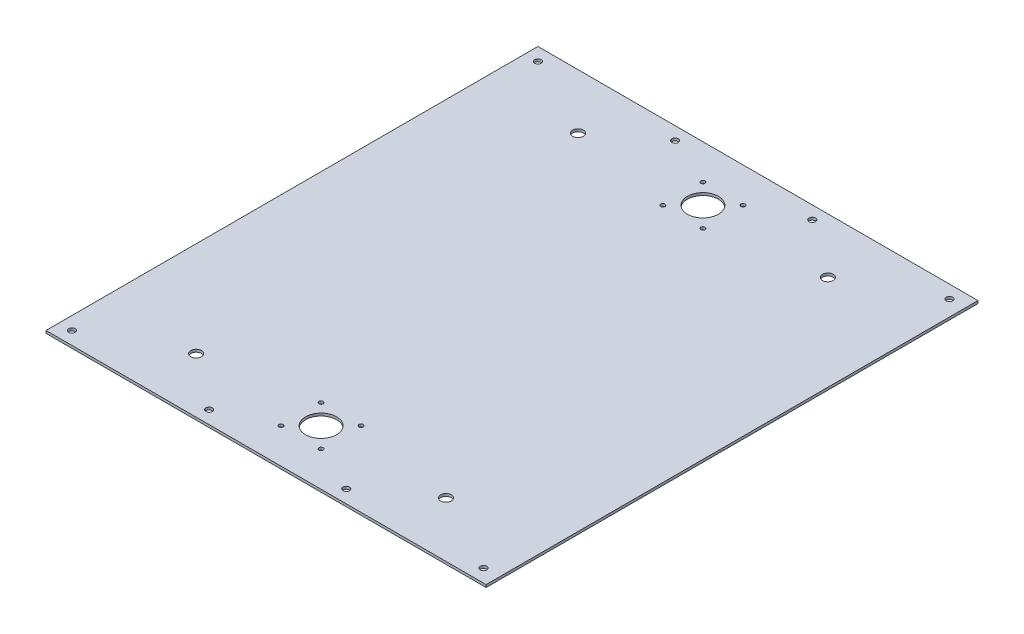
SolidWorks part; units mm, degrees
material "3.0526 (EN-AW 3004)"
ref_plane "Přední rovina" through (0, 0, 0) normal (0, 0, 1) x (1, 0, 0)
ref_plane "Horní rovina" through (0, 0, 0) normal (0, 1, 0) x (1, 0, 0)
ref_plane "Pravá rovina" through (0, 0, 0) normal (1, 0, 0) x (0, 0, -1)
sketch "Skica1" plane through (0, 0, 0) normal (0, 1, 0) x (1, 0, 0)
  line L1 (170, -190) -> (-170, -190)
  line L2 (170, -190) -> (170, 190)
  line L3 (170, 190) -> (-170, 190)
  line L4 (-170, -190) -> (-170, 190)
  line L5 (170, -190) -> (-170, 190) construction
  line L6 (170, 190) -> (-170, -190) construction
  circle A0 centre (-160, 180) radius 2.5
  circle A1 centre (-54, 180) radius 2.5
  circle A2 centre (52, 180) radius 2.5
  circle A3 centre (158, 180) radius 2.5
  circle A4 centre (-54, -180) radius 2.5
  circle A5 centre (52, -180) radius 2.5
  circle A6 centre (158, -180) radius 2.5
  circle A7 centre (-160, -180) radius 2.5
  point P0 (0, 0)
  dimension "D5" = 5
  dimension "D1" = 340
  dimension "D2" = 380
  dimension "D3" = 10
  dimension "D4" = 10
  dimension "D6" = 4
  dimension "D7" = 2
extrude "Přidat vysunutím1" add sketch "Skica1" along normal blind 2
sketch "Skica2" plane through (0, 0, 0) normal (0, -1, 0) x (1, 0, 0)
  circle A0 centre (15.5, 163) radius 1.65
  circle A1 centre (-15.5, 163) radius 1.65
  circle A2 centre (-15.5, 132) radius 1.65
  circle A3 centre (15.5, 132) radius 1.65
  circle A4 centre (15.5, -163) radius 1.65
  circle A5 centre (-15.5, -163) radius 1.65
  circle A6 centre (-15.5, -132) radius 1.65
  circle A7 centre (15.5, -132) radius 1.65
  circle A8 centre (96.5, -147.5) radius 4.15
  circle A9 centre (-96.5, -147.5) radius 4.15
  circle A10 centre (-96.5, 147.5) radius 4.15
  circle A11 centre (96.5, 147.5) radius 4.15
  circle A12 centre (0, -147.5) radius 12
  circle A13 centre (0, 147.5) radius 12
  dimension "D5" = 24
  dimension "D1" = 2
  dimension "D2" = 2
  dimension "D3" = 2
  dimension "D4" = 2
extrude "Odebrat vysunutím1" cut sketch "Skica2" against normal blind 2
